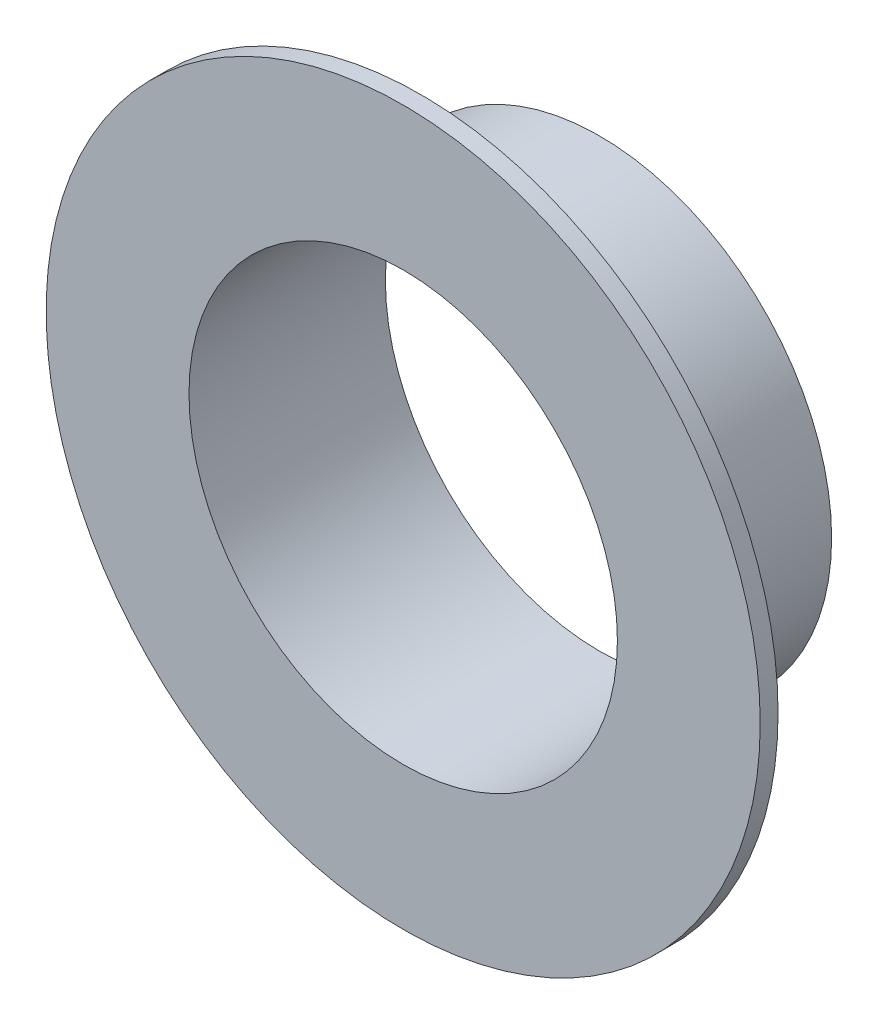
SolidWorks part; units mm, degrees
ref_plane "Plan1" through (0, 0, 0) normal (0, 0, 1) x (1, 0, 0)
ref_plane "Plan2" through (0, 0, 0) normal (0, 1, 0) x (1, 0, 0)
ref_plane "Plan3" through (0, 0, 0) normal (1, 0, 0) x (0, 0, -1)
sketch "Esquisse1" plane through (0, 0, 0) normal (0, 0, 1) x (1, 0, 0)
  circle A0 centre (0, 0) radius 6
  circle A1 centre (0, 0) radius 6.5
  dimension "D1" = 12
  dimension "D2" = 13
extrude "Base-Extrusion" add sketch "Esquisse1" along normal blind 5
sketch "Esquisse2" plane through (0, 0, 5) normal (0, 0, 1) x (1, 0, 0)
  circle A0 centre (0, 0) radius 6
  circle A1 centre (0, 0) radius 10
  dimension "D1" = 12
  dimension "D2" = 20
extrude "Boss.-Extru.1" add sketch "Esquisse2" along normal blind 0.5
